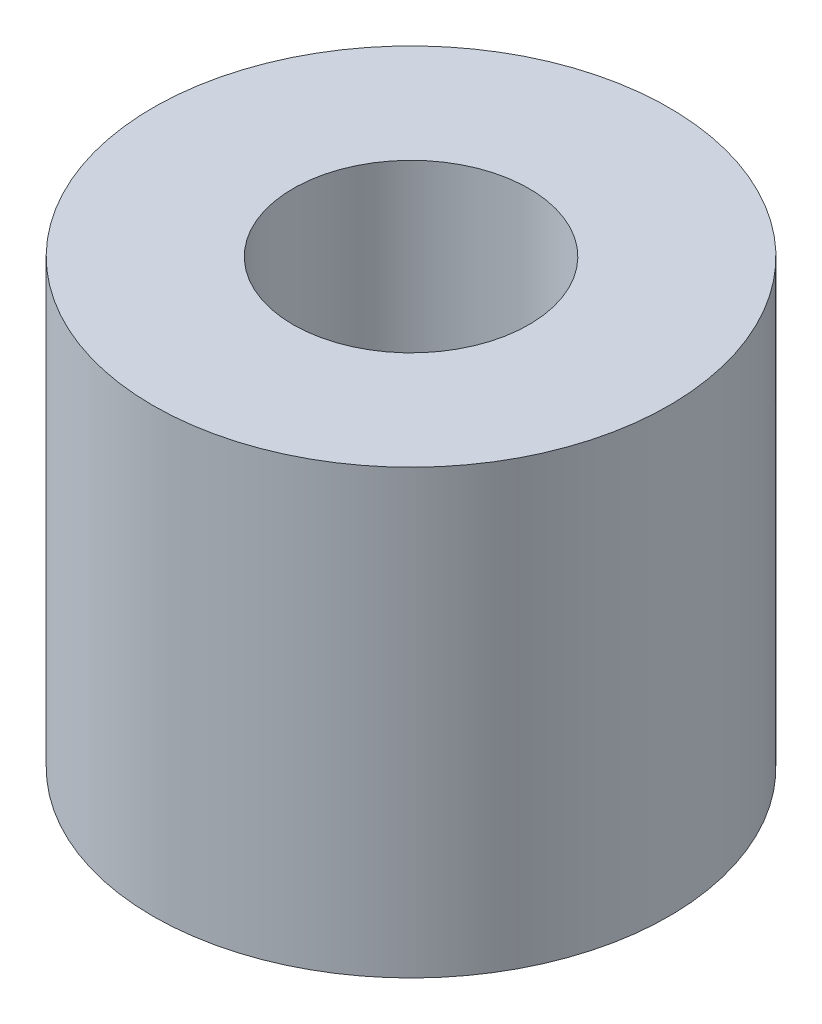
SolidWorks part; units mm, degrees
material "Автоматная латунь, UNS C36000"
ref_plane "Спереди" through (0, 0, 0) normal (0, 0, 1) x (1, 0, 0)
ref_plane "Сверху" through (0, 0, 0) normal (0, 1, 0) x (1, 0, 0)
ref_plane "Справа" through (0, 0, 0) normal (1, 0, 0) x (0, 0, -1)
sketch "Эскиз1" plane through (0, 0, 0) normal (0, 1, 0) x (1, 0, 0)
  circle A0 centre (0, 0) radius 1.75
  dimension "D1" = 3.5
extrude "Бобышка-Вытянуть1" add sketch "Эскиз1" along normal blind 3
hole_wizard "Отверстие обработанное метчиком M21" positions "Эскиз2" profile "Эскиз3" tap size "M2" standard "ISO" end condition through all
sketch "Эскиз2" plane through (0, 3, 0) normal (0, 1, 0) x (1, 0, 0)
  point P0 (0, 0)
sketch "Эскиз3" plane through (0, 3, 0) normal (1, 0, 0) x (0, 0, 1)
  line L0 (0, 0) -> (0, 3)
  line L1 (0, 3) -> (0.8, 3)
  line L2 (0.8, 3) -> (0.8, 0)
  line L5 (0.8, 0) -> (0, 0)
  line L11 (0, -6.35) -> (0, 107.95) construction
  dimension "Диаметр проходного сверла" = 1.6
  dimension "Глубина проходного сверла" = 3
cosmetic thread "Отверстие резьбы1" parameters "D2"=2
